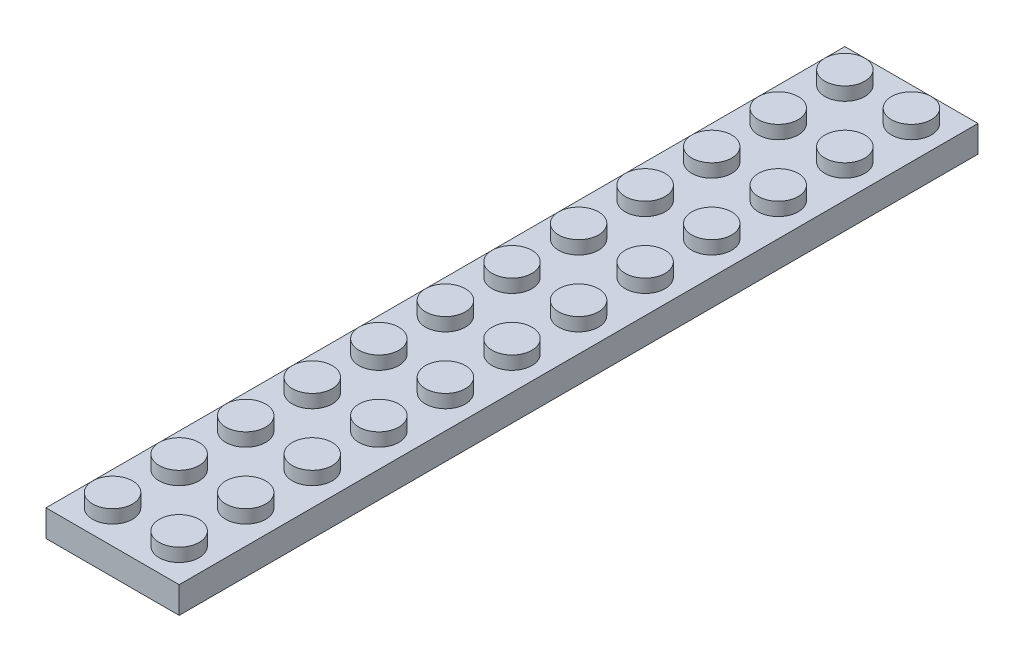
SolidWorks part; units mm, degrees
ref_plane "Front Plane" through (0, 0, 0) normal (0, 0, 1) x (1, 0, 0)
ref_plane "Top Plane" through (0, 0, 0) normal (0, 1, 0) x (1, 0, 0)
ref_plane "Right Plane" through (0, 0, 0) normal (1, 0, 0) x (0, 0, -1)
sketch "Sketch1" plane through (0, 0, 0) normal (0, 1, 0) x (1, 0, 0)
  line L1 (0, 0) -> (16, 0)
  line L2 (0, 0) -> (0, 96)
  line L3 (0, 96) -> (16, 96)
  line L4 (16, 0) -> (16, 96)
  dimension "D1" = 16
  dimension "D2" = 96
extrude "Boss-Extrude1" add sketch "Sketch1" along normal blind 3.2
sketch "Sketch2" plane through (0, 3.2, 0) normal (0, 1, 0) x (1, 0, 0)
  line L0 (8, 0) -> (8, 96) construction
  line L1 (0, 0) -> (16, 0) construction
  line L2 (16, 96) -> (0, 96) construction
  line L3 (16, 0) -> (16, 4) construction
  line L4 (16, 0) -> (16, 96) construction
  line L5 (16, 4) -> (12, 4) construction
  circle A0 centre (12, 4) radius 2.4
  dimension "D3" = 4.8
  dimension "D1" = 4
  dimension "D2" = 4
extrude "Boss-Extrude2" add sketch "Sketch2" along normal blind 1.6
pattern_linear "LPattern1" count 2 spacing 8 along (-1, 0, 0) count 12 spacing 8 along (0, 0, -1) of "Boss-Extrude2"
shell "Shell1" thickness 1.6
